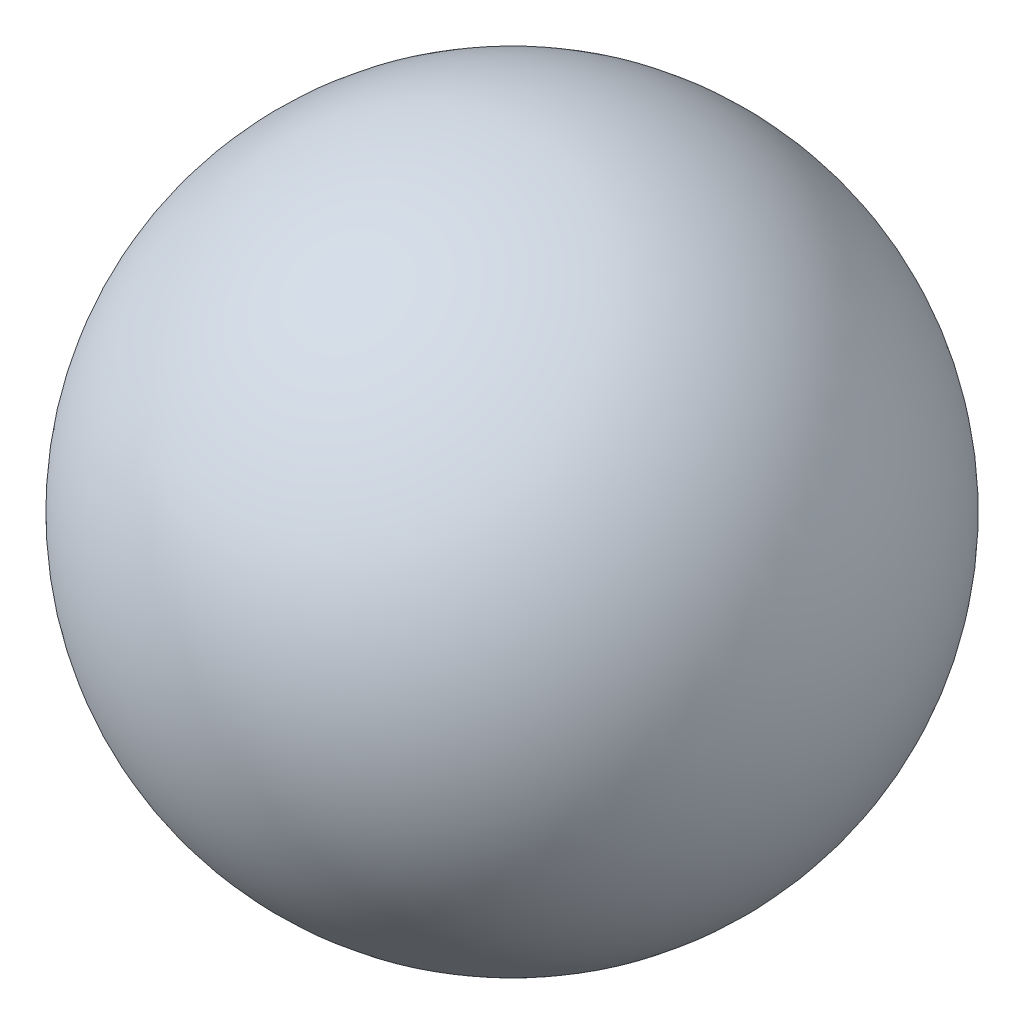
SolidWorks part; units mm, degrees
ref_plane "前视基准面" through (0, 0, 0) normal (0, 0, 1) x (1, 0, 0)
ref_plane "上视基准面" through (0, 0, 0) normal (0, 1, 0) x (1, 0, 0)
ref_plane "右视基准面" through (0, 0, 0) normal (1, 0, 0) x (0, 0, -1)
sketch "草图1" plane through (0, 0, 0) normal (0, 0, 1) x (1, 0, 0)
  line L0 (0, 12) -> (0, -12)
  arc A0 (0, -12) -> (0, 12) centre (0, 0) ccw
  dimension "D1" = 24
revolve "旋转1" add sketch "草图1" angle 360 about L0
